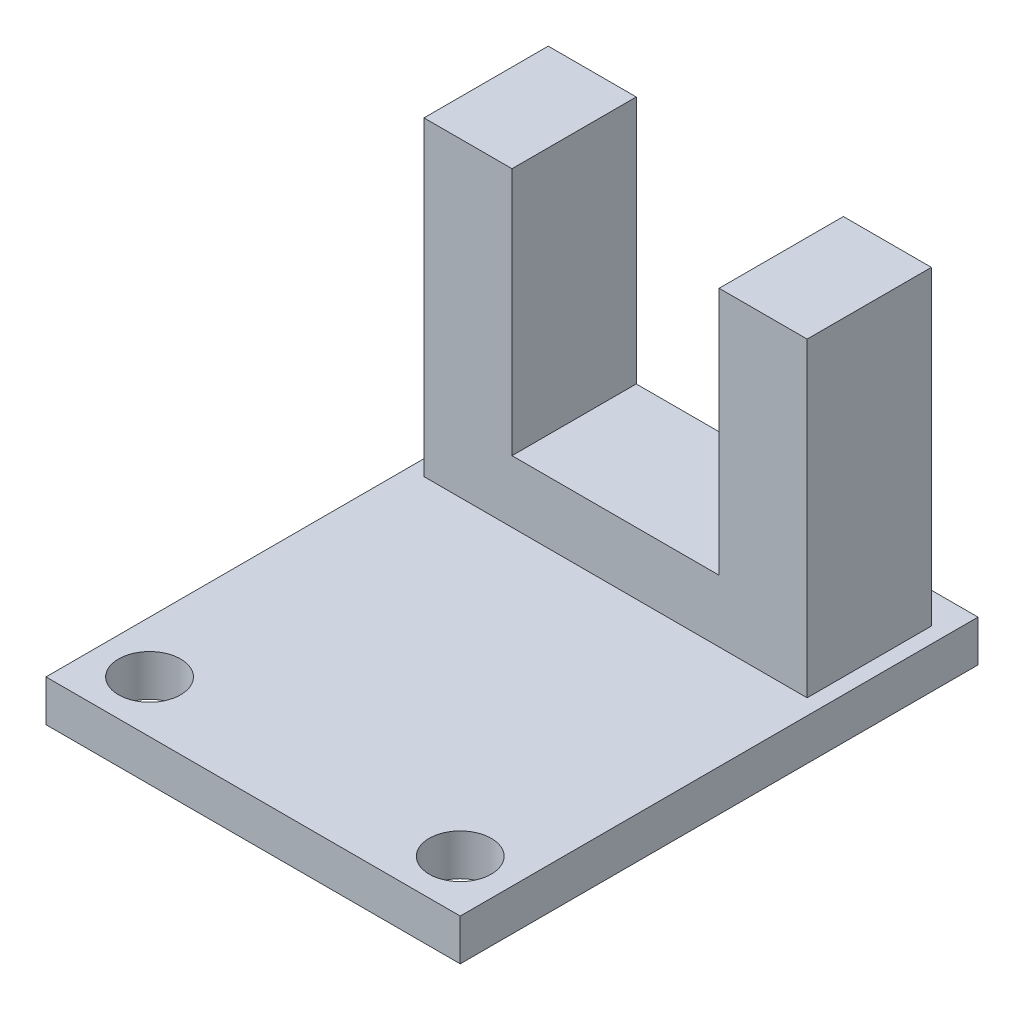
SolidWorks part; units mm, degrees
ref_plane "前基準面" through (0, 0, 0) normal (0, 0, 1) x (1, 0, 0)
ref_plane "上基準面" through (0, 0, 0) normal (0, 1, 0) x (1, 0, 0)
ref_plane "右基準面" through (0, 0, 0) normal (1, 0, 0) x (0, 0, -1)
ref_plane "平面1" through (0, -2, 0) normal (0, -1, 0) x (1, 0, 0)
sketch "草圖1" plane through (0, -2, 0) normal (0, -1, 0) x (1, 0, 0)
  line L0 (-10, 23.5) -> (-10, -1.5)
  line L1 (-10, -1.5) -> (10, -1.5)
  line L2 (10, -1.5) -> (10, 23.5)
  line L3 (10, 23.5) -> (-10, 23.5)
extrude "填料-伸長1" add sketch "草圖1" against normal blind 2
sketch "草圖2" plane through (0, 0, 0) normal (0, 1, 0) x (-1, 0, 0)
  line L0 (-9.25, 0) -> (-9.25, 6)
  line L1 (-9.25, 6) -> (9.25, 6)
  line L2 (9.25, 6) -> (9.25, 0)
  line L3 (9.25, 0) -> (-9.25, 0)
extrude "填料-伸長2" add sketch "草圖2" along normal blind 15
sketch "草圖3" plane through (0, 0, 0) normal (0, 0, -1) x (-1, 0, 0)
  line L0 (5, 15) -> (-5, 15)
  line L1 (-5, 15) -> (-5, 3)
  line L2 (-5, 3) -> (5, 3)
  line L3 (5, 3) -> (5, 15)
extrude "除料-伸長1" cut sketch "草圖3" against normal through all
hole_wizard "Ø3.0 (3) 直徑孔1" positions "草圖5" profile "草圖4" hole size "Ø3.0" standard "Ansi Metric"
sketch "草圖5" plane through (0, 0, 0) normal (0, 1, 0) x (1, 0, 0)
  point P0 (-7.5, -21)
  point P1 (7.5, -21)
sketch "草圖4" plane through (-7.5, 0, 21) normal (1, 0, 0) x (0, 0, 1)
  line L0 (0, 0) -> (0, 2)
  line L1 (0, 2) -> (1.5, 2)
  line L2 (1.5, 2) -> (1.5, 0)
  line L5 (1.5, 0) -> (0, 0)
  line L11 (0, -6.35) -> (0, 107.95) construction
  dimension "貫穿孔直徑" = 3
  dimension "貫穿孔深度" = 2
